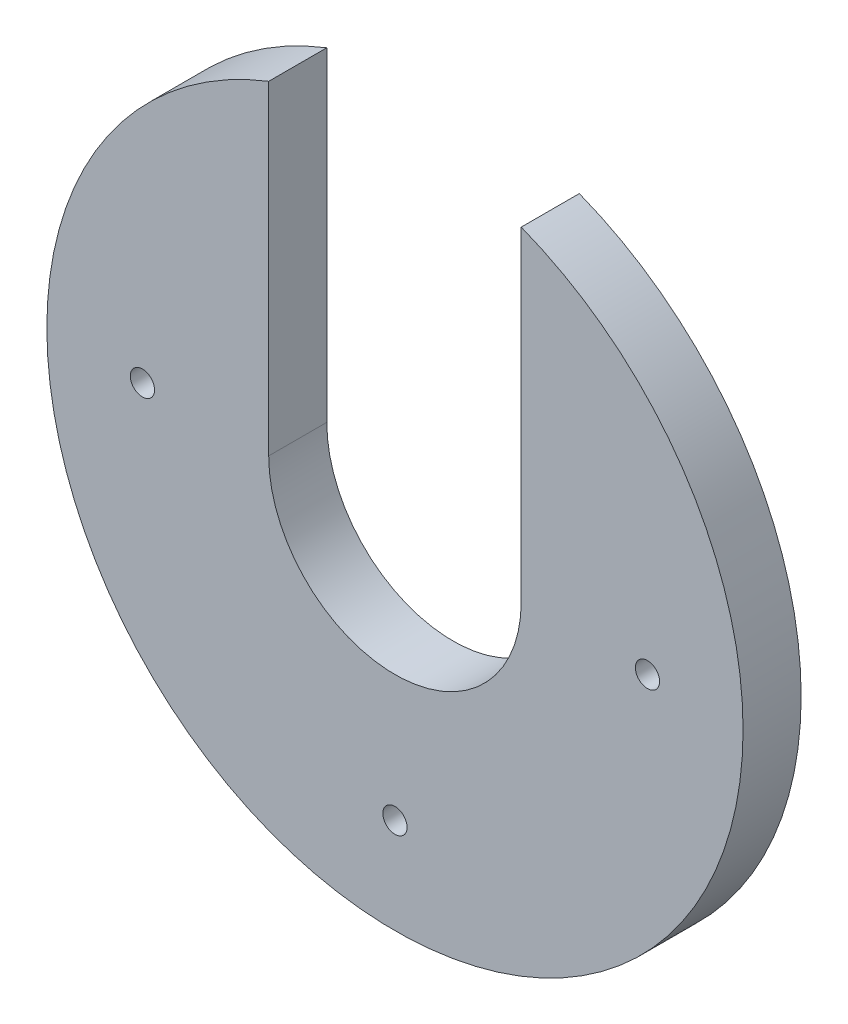
SolidWorks part; units mm, degrees
material "Beech"
ref_plane "Front Plane" through (0, 0, 0) normal (0, 0, 1) x (1, 0, 0)
ref_plane "Top Plane" through (0, 0, 0) normal (0, 1, 0) x (1, 0, 0)
ref_plane "Right Plane" through (0, 0, 0) normal (1, 0, 0) x (0, 0, -1)
sketch "Sketch1" plane through (0, 0, 0) normal (0, 0, 1) x (1, 0, 0)
  line L0 (0, 35.0139) -> (0, -35.0139) construction
  line L1 (-35.0139, 0) -> (35.0139, 0) construction
  line L2 (12.7, 0) -> (25.4, 0) construction
  line L3 (0, 0) -> (0, 25.4)
  line L4 (-12.7, 0) -> (-12.7, 32.6295)
  line L5 (12.7, 0) -> (12.7, 32.6295)
  circle A0 centre (0, 0) radius 35.0139
  circle A1 centre (0, 0) radius 12.7
  circle A2 centre (25.4, 0) radius 1.2192
  circle A3 centre (0, -25.4) radius 1.2192
  circle A4 centre (-25.4, 0) radius 1.2192
  circle A5 centre (0, 25.4) radius 1.2192 [skipped]
  point P20 (0, 0)
  point P29 (0, 0)
  dimension "D1" = 70.0278
  dimension "D2" = 25.4
  dimension "D4" = 2.4384
  dimension "D6" = 25.4
  dimension "D3" = 25.4
  dimension "D5" = 4
extrude "Boss-Extrude1" add sketch "Sketch1" along normal blind 5.842
